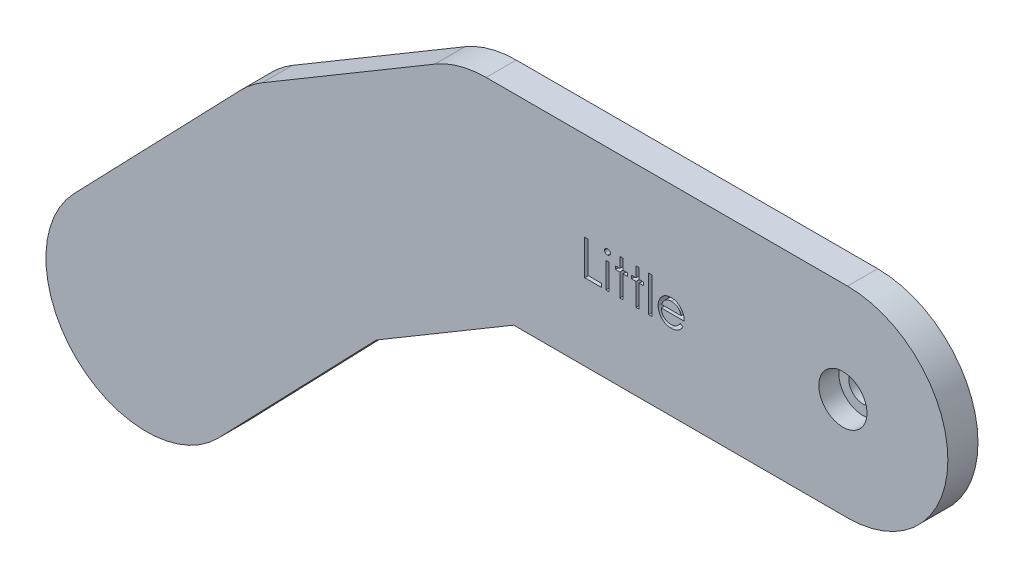
SolidWorks part; units mm, degrees
ref_plane "Front Plane" through (0, 0, 0) normal (0, 0, 1) x (1, 0, 0)
ref_plane "Top Plane" through (0, 0, 0) normal (0, 1, 0) x (1, 0, 0)
ref_plane "Right Plane" through (0, 0, 0) normal (1, 0, 0) x (0, 0, -1)
sketch "Sketch1" plane through (0, 0, 0) normal (0, 0, 1) x (1, 0, 0)
  line L0 (0, 0) -> (36, 0) construction
  line L2 (0, 10) -> (36, 10)
  line L3 (0, -10) -> (36, -10)
  arc A0 (0, 10) -> (0, -10) centre (0, 0) ccw
  arc A1 (36, -10) -> (36, 10) centre (36, 0) ccw
  point P5 (18, 0)
extrude "Boss-Extrude1" add sketch "Sketch1" along normal blind 3
sketch "Sketch2" plane through (0, 0, 0) normal (0, 0, 1) x (1, 0, 0)
  line L0 (0, 0) -> (-17.1984, -10.2085) construction
  line L2 (5.1043, -8.5992) -> (-12.0942, -18.8077)
  line L3 (-5.1043, 8.5992) -> (-22.3027, -1.6093)
  arc A0 (5.1043, -8.5992) -> (-5.1043, 8.5992) centre (0, 0) ccw
  arc A1 (-22.3027, -1.6093) -> (-12.0942, -18.8077) centre (-17.1984, -10.2085) ccw
  point P5 (-8.5992, -5.1043)
extrude "Boss-Extrude2" add sketch "Sketch2" along normal blind 3
sketch "Sketch3" plane through (0, 0, 0) normal (0, 0, 1) x (1, 0, 0)
  line L0 (-17.1984, -10.2085) -> (-33.8549, -27.4874) construction
  line L2 (-9.9989, -17.1487) -> (-26.6554, -34.4276)
  line L3 (-24.398, -3.2683) -> (-41.0545, -20.5472)
  arc A0 (-9.9989, -17.1487) -> (-24.398, -3.2683) centre (-17.1984, -10.2085) ccw
  arc A1 (-41.0545, -20.5472) -> (-26.6554, -34.4276) centre (-33.8549, -27.4874) ccw
  point P5 (-25.5267, -18.848)
extrude "Boss-Extrude4" add sketch "Sketch3" along normal blind 3
sketch "Sketch4" plane through (0, 0, 0) normal (0, 0, 1) x (1, 0, 0)
  circle A0 centre (35.5386, 0) radius 1.4
extrude "Cut-Extrude5" cut sketch "Sketch4" along normal blind 3
sketch "Sketch5" plane through (0, 0, 3) normal (0, 0, 1) x (1, 0, 0)
  circle A0 centre (35.5386, 0) radius 2.4
extrude "Cut-Extrude6" cut sketch "Sketch5" against normal blind 2
sketch "Sketch6" plane through (0, 0, 3) normal (0, 0, 1) x (1, 0, 0)
  text T0 "Little"
extrude "Cut-Extrude7" cut sketch "Sketch6" against normal blind 1
